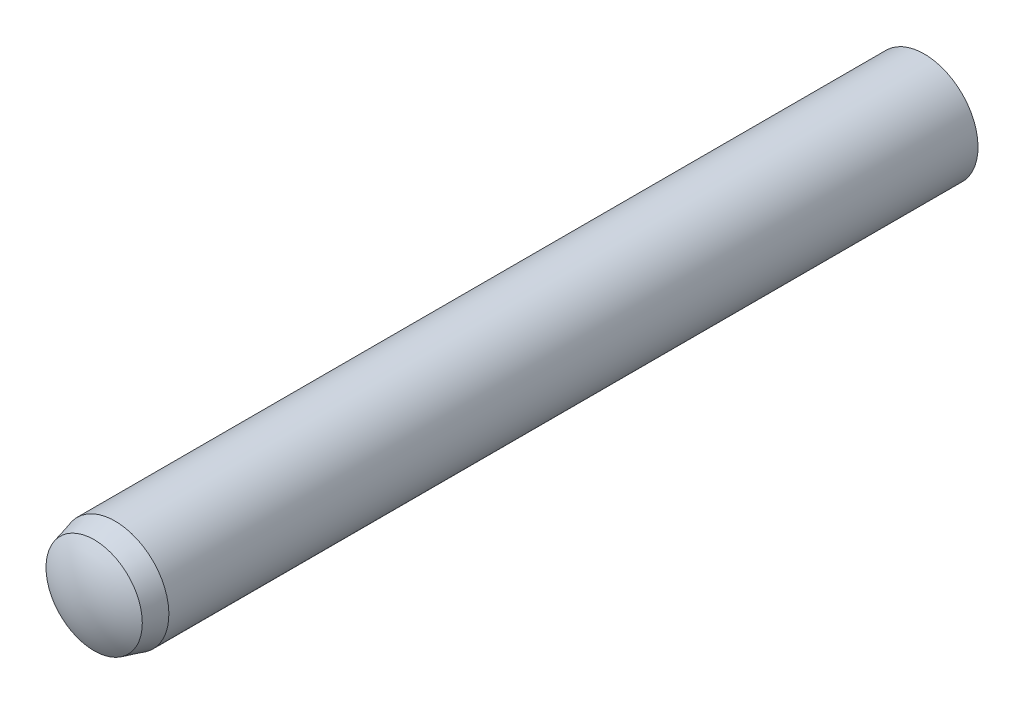
SolidWorks part; units mm, degrees
ref_plane "Front Plane" through (0, 0, 0) normal (0, 0, 1) x (1, 0, 0)
ref_plane "Top Plane" through (0, 0, 0) normal (0, 1, 0) x (1, 0, 0)
ref_plane "Right Plane" through (0, 0, 0) normal (1, 0, 0) x (0, 0, -1)
sketch "Sketch1" plane through (0, 0, 0) normal (0, 0, 1) x (1, 0, 0)
  circle A0 centre (0, 0) radius 1.25
  point P3 (0, 1.25)
  dimension "Diameter" = 2.5
sketch "Sketch2" plane through (0, 0, 0) normal (1, 0, 0) x (0, 0, -1)
  line L0 (-10, 0) -> (10, 0) construction
  line L1 (-10, 0) -> (-10, 1.25) construction
  line L2 (-10, 1.25) -> (10, 1.25)
  line L3 (10, 1.25) -> (10, 0) construction
  line L4 (-9.675, 1.1194) -> (-9.1875, 1.25)
  arc A0 (-10, 0) -> (-9.675, 1.1194) centre (-7.9098, 0) cw
  arc A1 (10, 0) -> (9.625, 1.25) centre (7.7292, 0) ccw
  point P2 (0, 0)
  point P11 (-7.5, 0)
  point P13 (7.5, 0)
  dimension "Length" = 20
  dimension "D1" = 15
  dimension "D2" = 0.375
  dimension "D3" = 0.8125
  dimension "D4" = 0.4875
  dimension "D5" = 2.5
  dimension "D6" = 2.5
sketch "Sketch3" plane through (0, 0, 0) normal (1, 0, 0) x (0, 0, -1)
  line L0 (-10, 0) -> (10, 0) construction
  line L1 (-9.675, 1.1194) -> (-9.1875, 1.25) construction
  line L2 (-10, 0) -> (10, 0)
  line L3 (-9.675, 1.1194) -> (-9.1875, 1.25)
  line L4 (-9.1875, 1.25) -> (9.625, 1.25)
  arc A0 (10, 0) -> (9.625, 1.25) centre (7.7292, 0) ccw construction
  arc A1 (-9.675, 1.1194) -> (-10, 0) centre (-7.9098, 0) ccw construction
  arc A2 (10, 0) -> (9.625, 1.25) centre (7.7292, 0) ccw
  arc A3 (-9.675, 1.1194) -> (-10, 0) centre (-7.9098, 0) ccw
revolve "Revolve1" add sketch "Sketch3" angle 360 about L2
equation "\"D2@Sketch2\" = \"Diameter@Sketch1\" * .15"
equation "\"D3@Sketch2\" = \"Diameter@Sketch1\" * .325"
equation "\"D4@Sketch2\" = \"D3@Sketch2\" * .6"
equation "\"D5@Sketch2\"=\"Diameter@Sketch1\""
equation "\"D6@Sketch2\"=\"D5@sketch2\""
